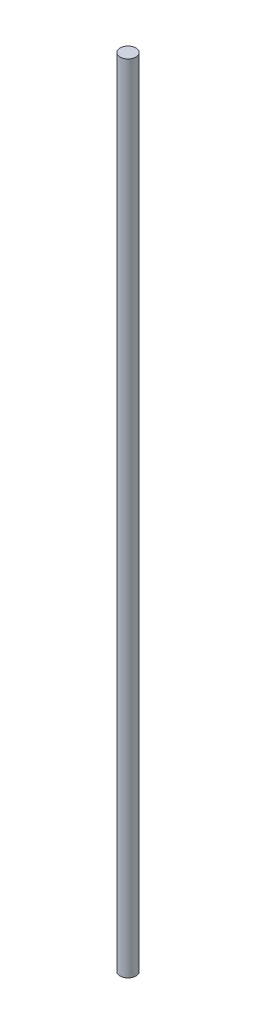
SolidWorks part; units mm, degrees
material "Chrome Stainless Steel"
ref_plane "Front Plane" through (0, 0, 0) normal (0, 0, 1) x (1, 0, 0)
ref_plane "Top Plane" through (0, 0, 0) normal (0, 1, 0) x (1, 0, 0)
ref_plane "Right Plane" through (0, 0, 0) normal (1, 0, 0) x (0, 0, -1)
sketch "Sketch1" plane through (0, 0, 0) normal (0, 1, 0) x (1, 0, 0)
  circle A0 centre (0, 0) radius 0.5
  dimension "D1" = 1
extrude "Extrude1" add sketch "Sketch1" along normal blind 45.5 and the other way blind 4.5
